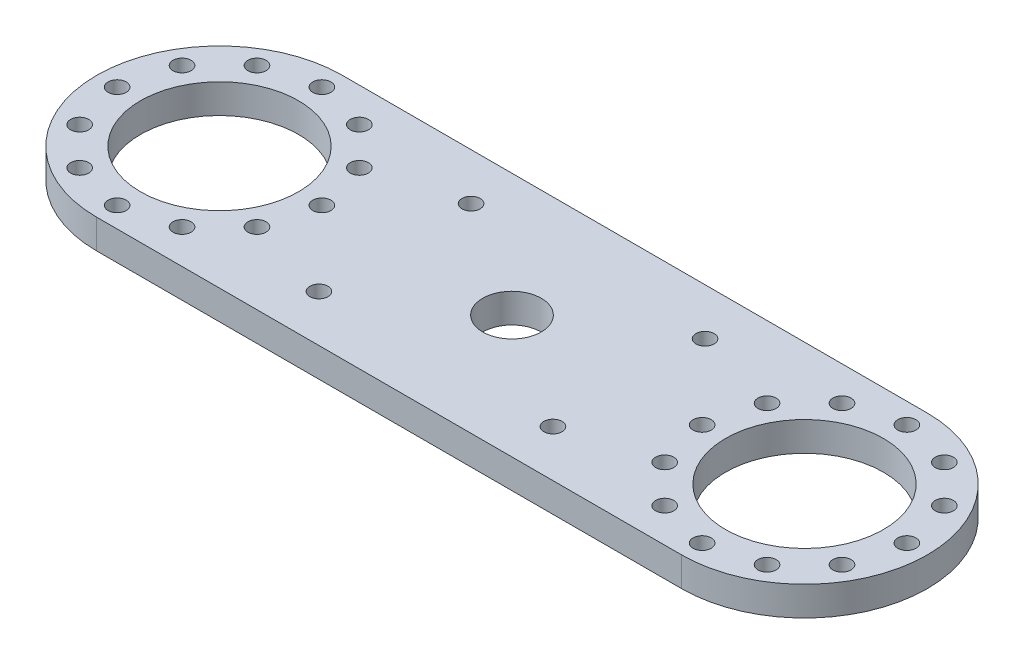
SolidWorks part; units mm, degrees
material "Thornel Mat VMA"
ref_plane "前视基准面" through (0, 0, 0) normal (0, 0, 1) x (1, 0, 0)
ref_plane "上视基准面" through (0, 0, 0) normal (0, 1, 0) x (1, 0, 0)
ref_plane "右视基准面" through (0, 0, 0) normal (1, 0, 0) x (0, 0, -1)
other "Configuration Table"
sketch "草图1" plane through (0, 0, 0) normal (0, 1, 0) x (1, 0, 0)
  line L0 (-50, 0) -> (50, 0) construction
  line L1 (-50, 21) -> (50, 21)
  line L2 (-50, -21) -> (50, -21)
  line L3 (0, -26.8061) -> (0, 32.763) construction
  arc A0 (-50, 21) -> (-50, -21) centre (-50, 0) ccw
  arc A1 (50, -21) -> (50, 21) centre (50, 0) ccw
  circle A2 centre (-50, 0) radius 13.5
  circle A3 centre (-50, 17.5) radius 1.55
  circle A4 centre (-20, 13) radius 1.55
  circle A5 centre (-20, -13) radius 1.55
  circle A6 centre (-41.25, 15.1554) radius 1.55
  circle A7 centre (-34.8446, 8.75) radius 1.55
  circle A8 centre (-32.5, 0) radius 1.55
  circle A9 centre (-34.8446, -8.75) radius 1.55
  circle A10 centre (-41.25, -15.1554) radius 1.55
  circle A11 centre (-50, -17.5) radius 1.55
  circle A12 centre (-58.75, -15.1554) radius 1.55
  circle A13 centre (-65.1554, -8.75) radius 1.55
  circle A14 centre (-67.5, 0) radius 1.55
  circle A15 centre (-65.1554, 8.75) radius 1.55
  circle A16 centre (-58.75, 15.1554) radius 1.55
  circle A17 centre (58.75, 15.1554) radius 1.55
  circle A18 centre (65.1554, 8.75) radius 1.55
  circle A19 centre (67.5, 0) radius 1.55
  circle A20 centre (65.1554, -8.75) radius 1.55
  circle A21 centre (58.75, -15.1554) radius 1.55
  circle A22 centre (50, -17.5) radius 1.55
  circle A23 centre (41.25, -15.1554) radius 1.55
  circle A24 centre (34.8446, -8.75) radius 1.55
  circle A25 centre (32.5, 0) radius 1.55
  circle A26 centre (41.25, 15.1554) radius 1.55
  circle A27 centre (20, -13) radius 1.55
  circle A28 centre (20, 13) radius 1.55
  circle A29 centre (50, 17.5) radius 1.55
  circle A30 centre (50, 0) radius 13.5
  circle A31 centre (34.8446, 8.75) radius 1.55
  point P2 (0, 0)
  point P40 (-50, 0)
  point P67 (50, 0)
  dimension "D2" = 21
  dimension "D3" = 27
  dimension "D5" = 3.1
  dimension "D9" = 3.1
  dimension "D1" = 100
  dimension "D4" = 17.5
  dimension "D6" = 26
  dimension "D7" = 20
  dimension "D8" = 13
  dimension "D10" = 12
extrude "凸台-拉伸1" add sketch "草图1" along normal blind 5
sketch "草图2" plane through (0, 5, 0) normal (0, 1, 0) x (1, 0, 0)
  circle A0 centre (0, 0) radius 5
  dimension "D1" = 10
extrude "切除-拉伸1" cut sketch "草图2" against normal blind 5
